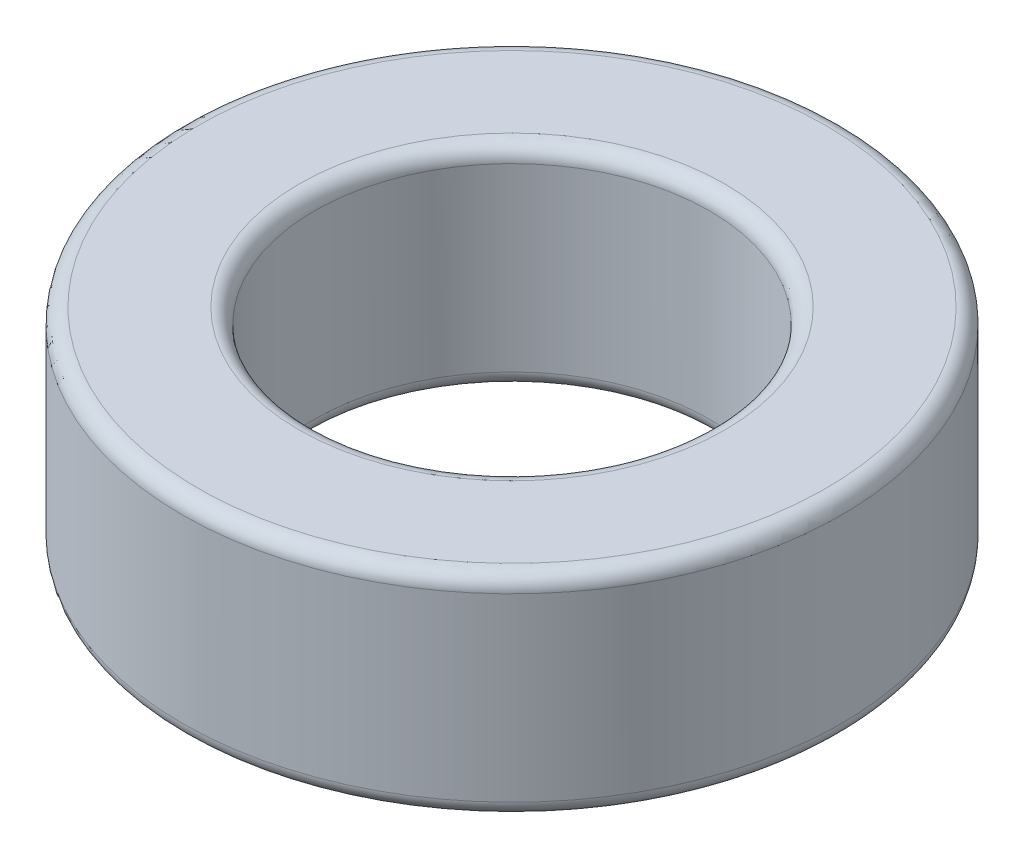
SolidWorks part; units mm, degrees
ref_plane "Front Plane" through (0, 0, 0) normal (0, 0, 1) x (1, 0, 0)
ref_plane "Top Plane" through (0, 0, 0) normal (0, 1, 0) x (1, 0, 0)
ref_plane "Right Plane" through (0, 0, 0) normal (1, 0, 0) x (0, 0, -1)
sketch "Sketch1" plane through (0, 0, 0) normal (0, 0, 1) x (1, 0, 0)
  line L0 (0, 15.8866) -> (0, -19.4169) construction
  line L2 (12.75, 6.825) -> (21.275, 6.825)
  line L3 (12.75, 6.825) -> (12.75, -6.825)
  line L4 (12.75, -6.825) -> (21.275, -6.825)
  line L5 (21.275, 6.825) -> (21.275, -6.825)
  line L6 (12.75, 6.825) -> (21.275, -6.825) construction
  line L7 (12.75, -6.825) -> (21.275, 6.825) construction
  point P3 (17.0125, 0)
  point P8 (0, 0)
  dimension "D1" = 42.55
  dimension "D2" = 25.5
  dimension "D3" = 13.65
revolve "Revolve1" add sketch "Sketch1" angle 360 about L0
fillet "Fillet1" radius 1 4 edges at (0, -6.825, 12.75) (0, -6.825, 21.275) (0, 6.825, 21.275) (0, 6.825, 12.75)
